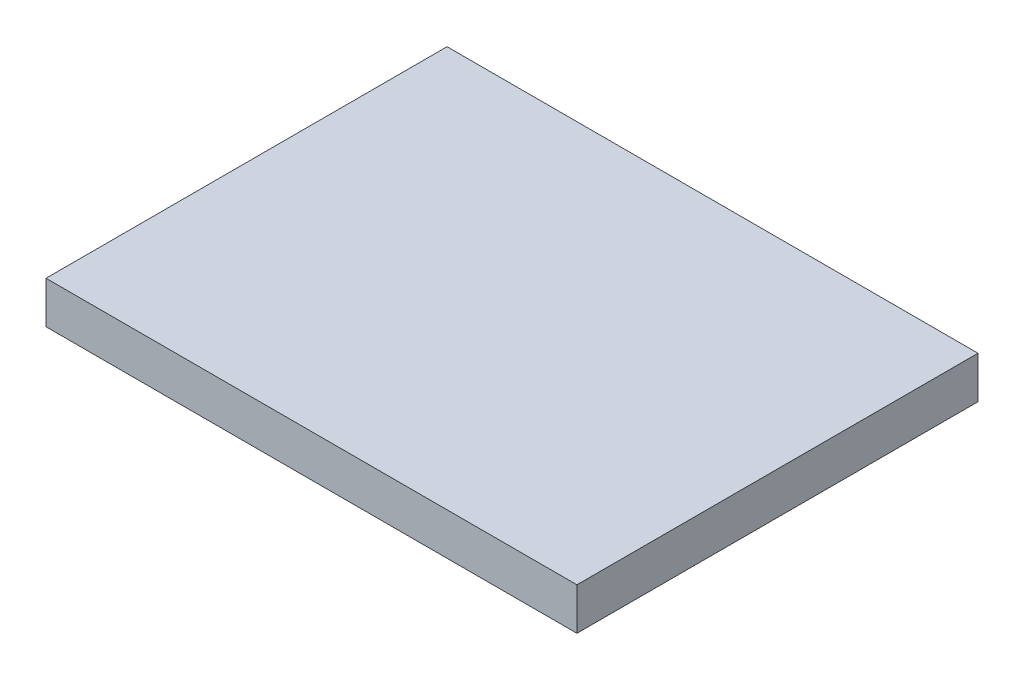
SolidWorks part; units mm, degrees
ref_plane "Front Plane" through (0, 0, 0) normal (0, 0, 1) x (1, 0, 0)
ref_plane "Top Plane" through (0, 0, 0) normal (0, 1, 0) x (1, 0, 0)
ref_plane "Right Plane" through (0, 0, 0) normal (1, 0, 0) x (0, 0, -1)
sketch "Sketch1" plane through (0, 0, 0) normal (0, 1, 0) x (1, 0, 0)
  line L1 (-88.265, -66.675) -> (88.265, -66.675)
  line L2 (-88.265, -66.675) -> (-88.265, 66.675)
  line L3 (-88.265, 66.675) -> (88.265, 66.675)
  line L4 (88.265, -66.675) -> (88.265, 66.675)
  line L5 (-88.265, -66.675) -> (88.265, 66.675) construction
  line L6 (-88.265, 66.675) -> (88.265, -66.675) construction
  point P0 (0, 0)
  dimension "D1" = 176.53
  dimension "D2" = 133.35
extrude "Boss-Extrude1" add sketch "Sketch1" along normal blind 13.97
